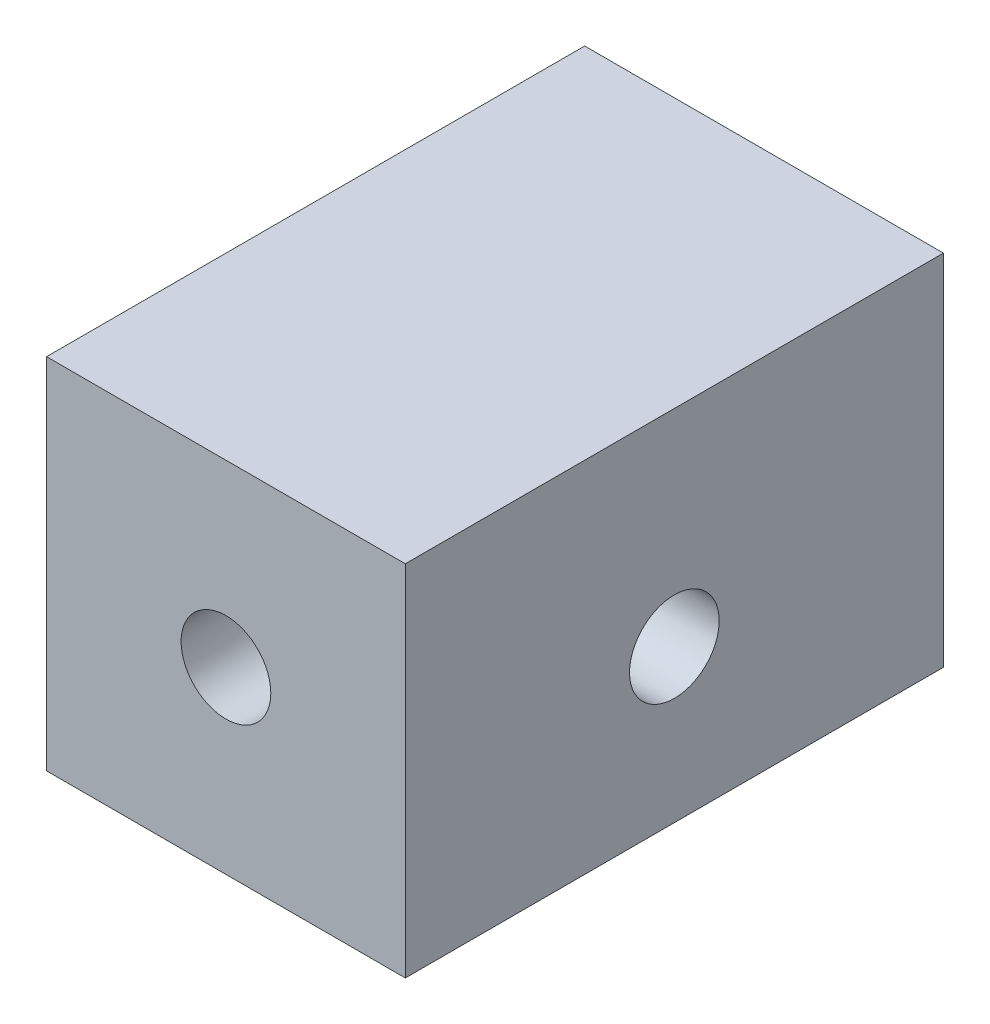
SolidWorks part; units mm, degrees
ref_plane "Front Plane" through (0, 0, 0) normal (0, 0, 1) x (1, 0, 0)
ref_plane "Top Plane" through (0, 0, 0) normal (0, 1, 0) x (1, 0, 0)
ref_plane "Right Plane" through (0, 0, 0) normal (1, 0, 0) x (0, 0, -1)
sketch "Sketch1" plane through (0, 0, 0) normal (0, 0, 1) x (1, 0, 0)
  line L1 (-12.7, -12.7) -> (12.7, -12.7)
  line L2 (-12.7, -12.7) -> (-12.7, 12.7)
  line L3 (-12.7, 12.7) -> (12.7, 12.7)
  line L4 (12.7, -12.7) -> (12.7, 12.7)
  line L5 (-12.7, -12.7) -> (12.7, 12.7) construction
  line L6 (-12.7, 12.7) -> (12.7, -12.7) construction
  point P0 (0, 0)
  dimension "D1" = 25.4
  dimension "D2" = 25.4
extrude "Boss-Extrude1" add sketch "Sketch1" along normal blind 38.1
sketch "Sketch2" plane through (-12.7, 0, 0) normal (-1, 0, 0) x (0, 0, 1)
  line L1 (38.1, -12.7) -> (38.1, 12.7) construction
  line L2 (38.1, -12.7) -> (0, -12.7) construction
  circle A0 centre (19.05, -1.905) radius 3.175
  dimension "D1" = 19.05
  dimension "D2" = 6.35
  dimension "D3" = 10.795
sketch "Sketch3" plane through (0, 0, 38.1) normal (0, 0, 1) x (1, 0, 0)
  circle A0 centre (0, 0) radius 3.175
  dimension "D1" = 6.35
extrude "Cut-Extrude1" cut sketch "Sketch3" against normal blind 12.7
extrude "Cut-Extrude2" cut sketch "Sketch2" against normal through all contours A0
